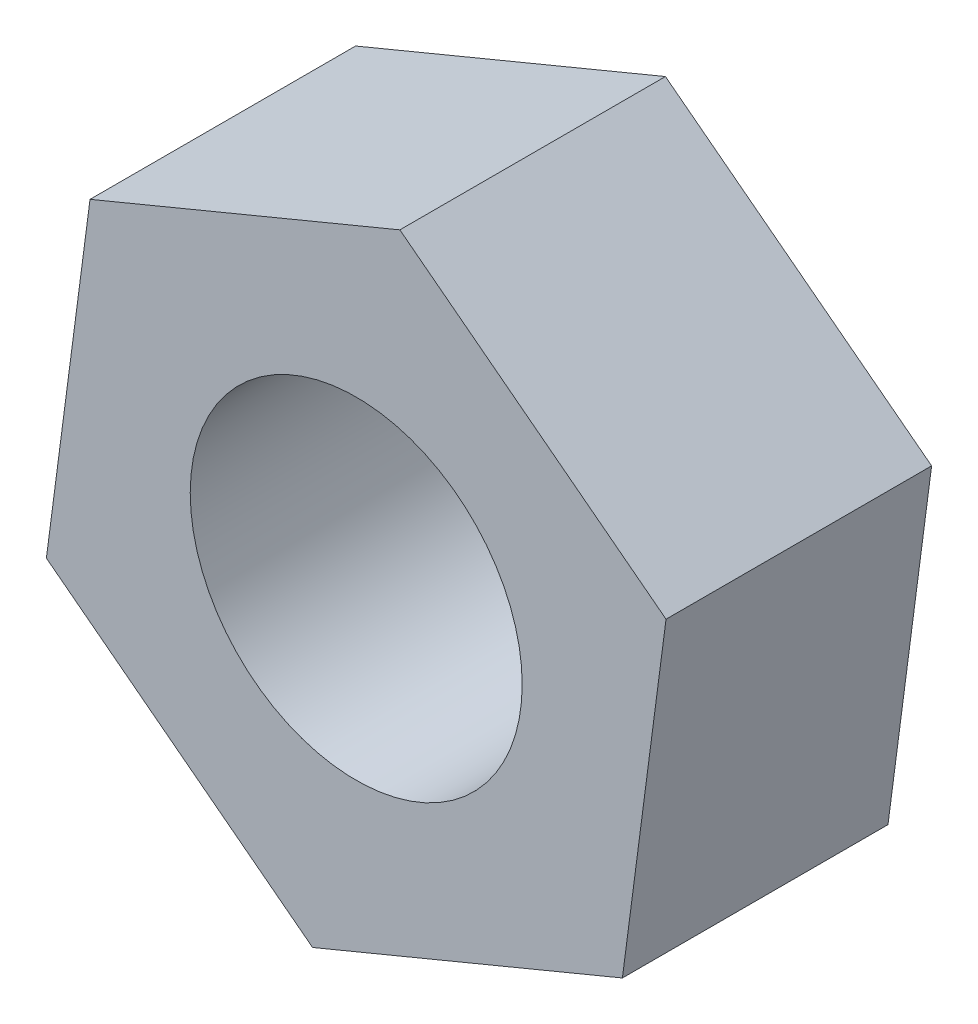
SolidWorks part; units mm, degrees
ref_plane "前视基准面" through (0, 0, 0) normal (0, 0, 1) x (1, 0, 0)
ref_plane "上视基准面" through (0, 0, 0) normal (0, 1, 0) x (1, 0, 0)
ref_plane "右视基准面" through (0, 0, 0) normal (1, 0, 0) x (0, 0, -1)
ref_plane "基准面4" through (0, 0, -28.5) normal (0, 0, 1) x (1, 0, 0)
sketch "草图1" plane through (0, 0, -28.5) normal (0, 0, 1) x (1, 0, 0)
  line L0 (9.5259, -15.9929) -> (5.7927, -17.541)
  line L1 (5.7927, -17.541) -> (5.2668, -21.5481)
  line L2 (5.2668, -21.5481) -> (8.4741, -24.0071)
  line L3 (8.4741, -24.0071) -> (12.2073, -22.459)
  line L4 (12.2073, -22.459) -> (12.7332, -18.4519)
  line L5 (12.7332, -18.4519) -> (9.5259, -15.9929)
  circle A0 centre (9, -20) radius 2
extrude "凸台-拉伸1" add sketch "草图1" against normal blind 3.2
